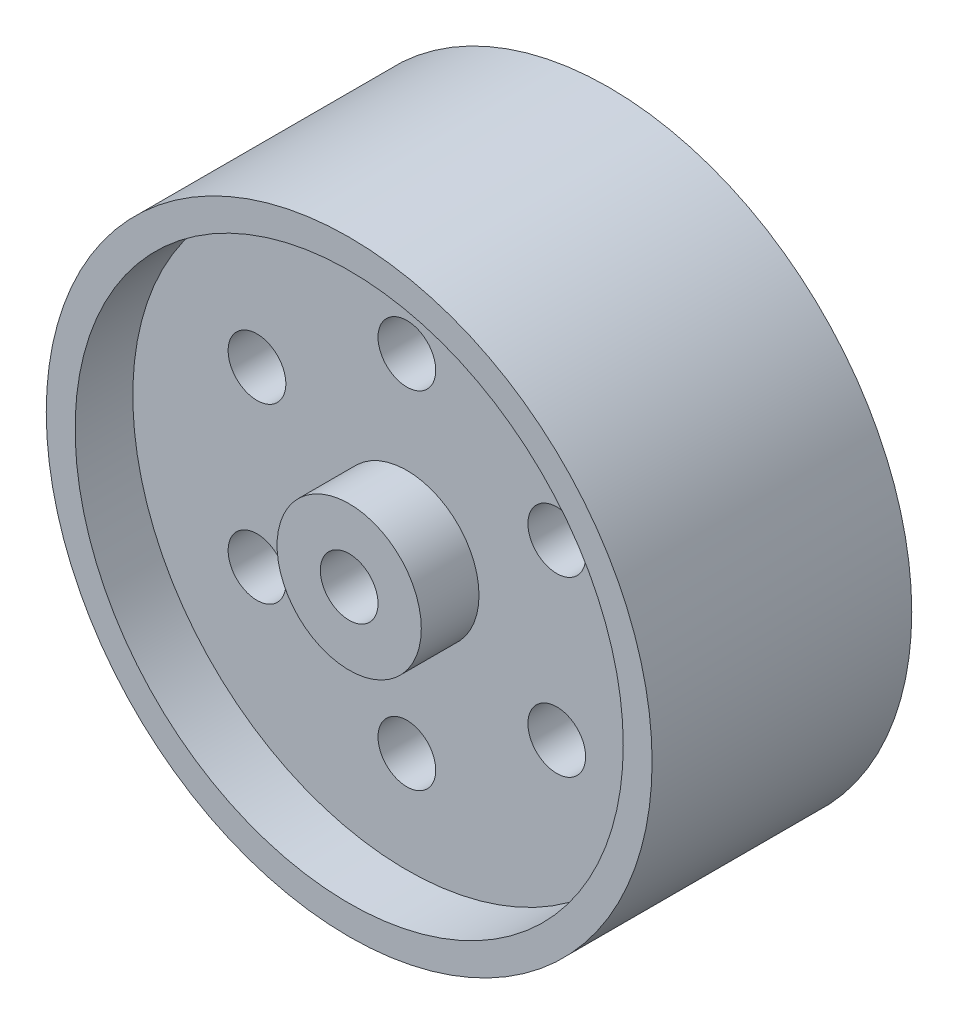
SolidWorks part; units mm, degrees
ref_plane "Front Plane" through (0, 0, 0) normal (0, 0, 1) x (1, 0, 0)
ref_plane "Top Plane" through (0, 0, 0) normal (0, 1, 0) x (1, 0, 0)
ref_plane "Right Plane" through (0, 0, 0) normal (1, 0, 0) x (0, 0, -1)
sketch "Sketch1" plane through (0, 0, 0) normal (1, 0, 0) x (0, 0, -1)
  line L0 (-6.2637, 0) -> (6.5363, 0) construction
  line L1 (-7, 2) -> (-7, 5)
  line L2 (-3, 5) -> (-3, 19)
  line L3 (-3, 19) -> (-7, 19)
  line L4 (-7, 19) -> (-7, 21)
  line L5 (-7, 21) -> (11, 21)
  line L6 (11, 21) -> (11, 15)
  line L7 (11, 15) -> (7, 15)
  line L8 (7, 15) -> (7, 2)
  line L9 (7, 2) -> (-7, 2)
  line L10 (-7, 5) -> (-3, 5)
  dimension "D1" = 2
  dimension "D2" = 5
  dimension "D3" = 21
  dimension "D4" = 19
  dimension "D5" = 15
  dimension "D6" = 4
  dimension "D7" = 4
  dimension "D8" = 14
  dimension "D9" = 18
revolve "Revolve1" add sketch "Sketch1" angle 360 about L0
sketch "Sketch2" plane through (0, 0, -7) normal (0, 0, -1) x (-1, 0, 0)
  circle A0 centre (0, 0) radius 12 construction
  circle A1 centre (0, 12) radius 2
  circle A2 centre (10.3923, 6) radius 2
  circle A3 centre (10.3923, -6) radius 2
  circle A4 centre (0, -12) radius 2
  circle A5 centre (-10.3923, -6) radius 2
  circle A6 centre (-10.3923, 6) radius 2
  point P17 (0, 0)
  dimension "D1" = 24
  dimension "D2" = 4
  dimension "D3" = 6
extrude "Cut-Extrude3" cut sketch "Sketch2" against normal through all
